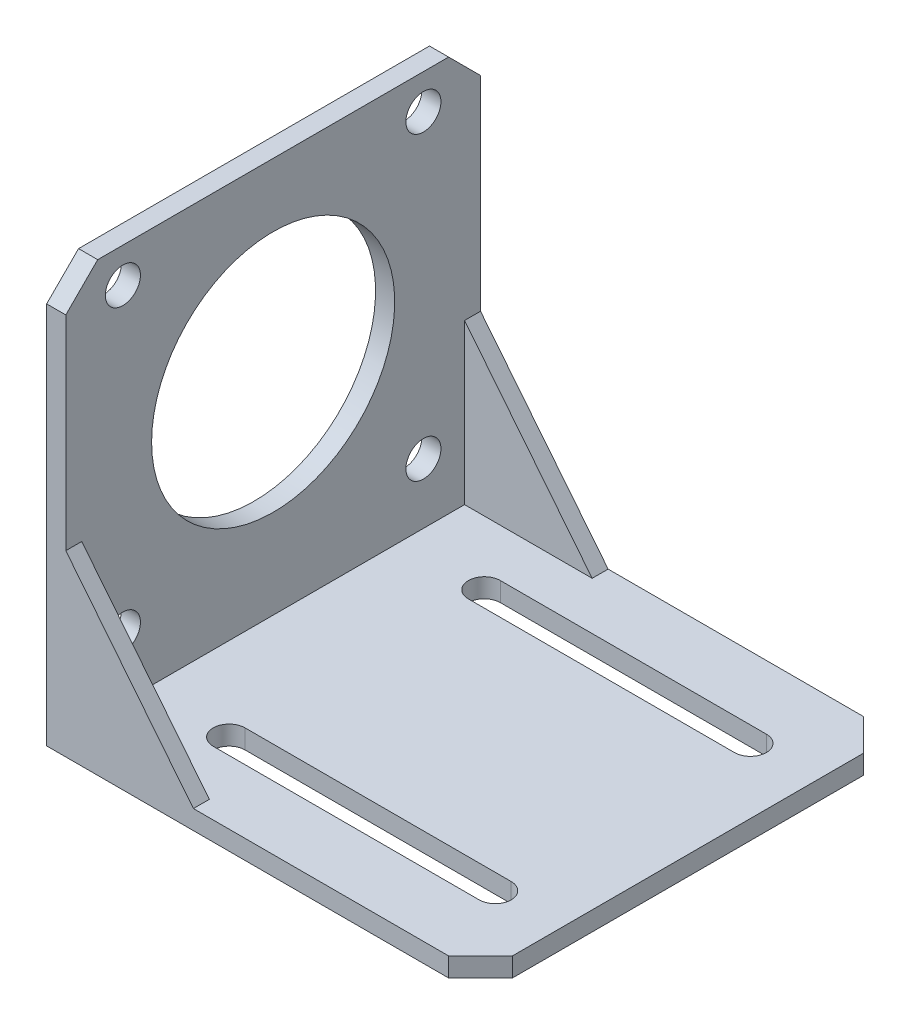
SolidWorks part; units mm, degrees
ref_plane "Front Plane" through (0, 0, 0) normal (0, 0, 1) x (1, 0, 0)
ref_plane "Top Plane" through (0, 0, 0) normal (0, 1, 0) x (1, 0, 0)
ref_plane "Right Plane" through (0, 0, 0) normal (1, 0, 0) x (0, 0, -1)
sketch "Sketch2" plane through (0, 0, 0) normal (0, 1, 0) x (1, 0, 0)
  line L1 (-34, 32.5) -> (34, 32.5)
  line L2 (-34, 32.5) -> (-34, -32.5)
  line L3 (-34, -32.5) -> (34, -32.5)
  line L4 (34, 32.5) -> (34, -32.5)
  line L5 (-34, 32.5) -> (34, -32.5) construction
  line L6 (-34, -32.5) -> (34, 32.5) construction
  point P0 (0, 0)
  dimension "D1" = 68
  dimension "D2" = 65
extrude "Boss-Extrude1" add sketch "Sketch2" along normal blind 3
sketch "Sketch3" plane through (0, 3, 0) normal (0, 1, 0) x (1, 0, 0)
  line L0 (-34, -32.5) -> (34, -32.5) construction
  line L2 (-34, 32.5) -> (-31, 32.5)
  line L3 (-34, 32.5) -> (-34, -32.5)
  line L4 (-34, -32.5) -> (-31, -32.5)
  line L5 (-31, 32.5) -> (-31, -32.5)
  dimension "D1" = 3
extrude "Boss-Extrude2" add sketch "Sketch3" along normal blind 62
sketch "Sketch4" plane through (0, 3, 0) normal (0, 1, 0) x (1, 0, 0)
  line L0 (-17.9, 22.5) -> (23.8, 22.5)
  line L1 (-17.9, 17.5) -> (23.8, 17.5)
  line L2 (-17.9, -17.5) -> (23.8, -17.5)
  line L3 (-17.9, -22.5) -> (23.8, -22.5)
  line L4 (34, -32.5) -> (34, 32.5) construction
  line L5 (34, 32.5) -> (-31, 32.5) construction
  arc A0 (-17.9, 22.5) -> (-17.9, 17.5) centre (-17.9, 20) ccw
  arc A1 (23.8, 22.5) -> (23.8, 17.5) centre (23.8, 20) cw
  arc A2 (-17.9, -17.5) -> (-17.9, -22.5) centre (-17.9, -20) ccw
  arc A3 (23.8, -17.5) -> (23.8, -22.5) centre (23.8, -20) cw
  dimension "D7" = 2.5
  dimension "D8" = 2.5
  dimension "D1" = 41.7
  dimension "D2" = 41.7
  dimension "D3" = 10.2
  dimension "D4" = 10.2
  dimension "D5" = 40
  dimension "D6" = 12.5
extrude "Cut-Extrude1" cut sketch "Sketch4" against normal through all
sketch "Sketch5" plane through (-34, 0, 0) normal (-1, 0, 0) x (0, 0, 1)
  line L0 (-32.5, 65) -> (32.5, 65) construction
  circle A0 centre (0, 36) radius 19.05
  dimension "D1" = 38.1
  dimension "D2" = 29
extrude "Cut-Extrude2" cut sketch "Sketch5" against normal through all
hole_wizard "Ø5.5 (5.5) Diameter Hole1" positions "Sketch7" profile "Sketch6" hole size "Ø5.5" standard "ISO" end condition through all
sketch "Sketch7" plane through (-34, 0, 0) normal (-1, 0, 0) x (0, 0, 1)
  line L0 (-32.5, 65) -> (-32.5, 0) construction
  line L1 (-32.5, 65) -> (32.5, 65) construction
  point P0 (23.55, 59.55)
  point P2 (-23.55, 59.55)
  point P4 (-23.55, 12.45)
  point P6 (23.55, 12.45)
  dimension "D1" = 47.1
  dimension "D2" = 47.1
  dimension "D3" = 8.95
  dimension "D4" = 8.95
  dimension "D5" = 47.1
  dimension "D6" = 47.1
  dimension "D7" = 5.45
sketch "Sketch6" plane through (-34, 59.55, 23.55) normal (0, 1, 0) x (0, 0, 1)
  line L0 (0, 0) -> (0, 68)
  line L1 (0, 68) -> (2.75, 68)
  line L2 (2.75, 68) -> (2.75, 0)
  line L5 (2.75, 0) -> (0, 0)
  line L11 (0, -6.35) -> (0, 107.95) construction
  dimension "Thru Hole Dia." = 5.5
  dimension "Thru Hole Depth" = 68
chamfer "Chamfer1" distance 5 angle 45 1 edges at (-32.5, 65, -32.5)
chamfer "Chamfer2" distance 5 angle 45 1 edges at (-32.5, 65, 32.5)
chamfer "Chamfer3" distance 5 angle 45 2 edges at (34, 1.5, 32.5) (34, 1.5, -32.5)
ref_plane "Plane1" through (0, 0, 32.5) normal (0, 0, 1) x (1, 0, 0)
sketch "Sketch8" plane through (0, 0, 32.5) normal (0, 0, 1) x (1, 0, 0)
  line L0 (-31, 3) -> (-31, 28)
  line L1 (-31, 60) -> (-31, 3) construction
  line L2 (-31, 28) -> (-11, 3)
  line L3 (-31, 3) -> (29, 3) construction
  line L4 (-11, 3) -> (-31, 3)
  dimension "D1" = 25
  dimension "D2" = 20
extrude "Boss-Extrude3" add sketch "Sketch8" against normal blind 2.5
ref_plane "Plane2" through (0, 0, -32.5) normal (0, 0, -1) x (-1, 0, 0)
sketch "Sketch9" plane through (0, 0, -32.5) normal (0, 0, -1) x (-1, 0, 0)
  line L0 (31, 3) -> (31, 28)
  line L1 (31, 60) -> (31, 3) construction
  line L2 (31, 28) -> (11, 3)
  line L3 (-29, 3) -> (31, 3) construction
  line L4 (11, 3) -> (31, 3)
  dimension "D1" = 25
  dimension "D2" = 20
extrude "Boss-Extrude4" add sketch "Sketch9" against normal blind 2.5
